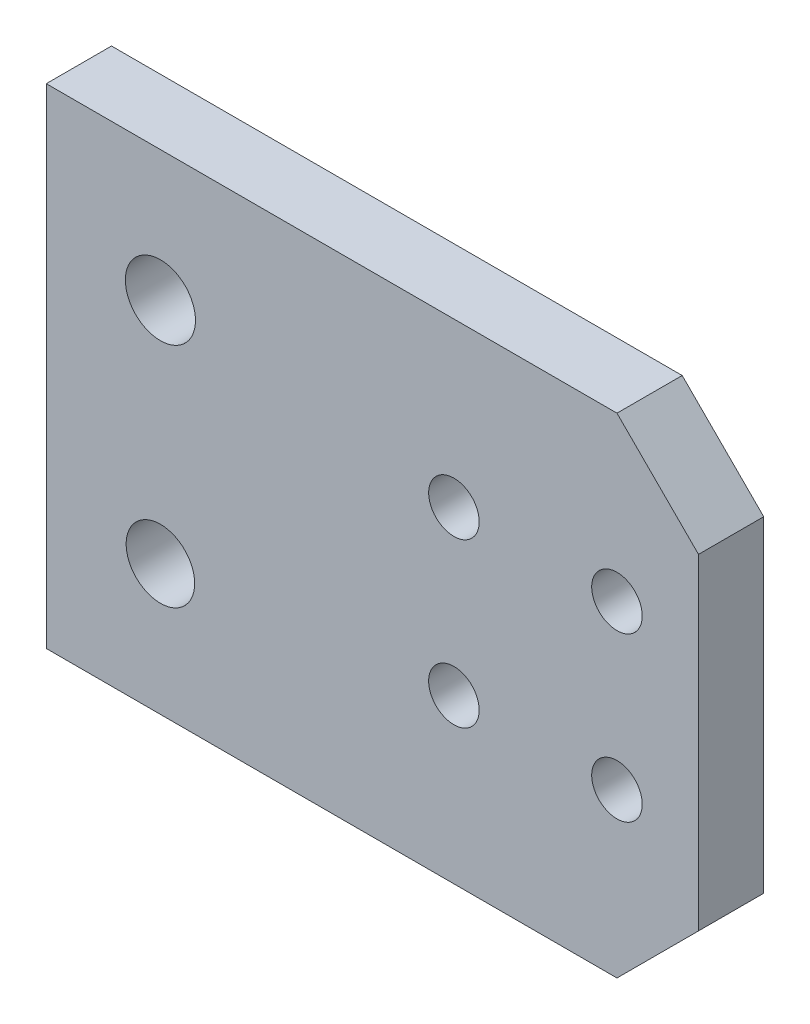
SolidWorks part; units mm, degrees
material "Thornel Mat VMA"
ref_plane "前视基准面" through (0, 0, 0) normal (0, 0, 1) x (1, 0, 0)
ref_plane "上视基准面" through (0, 0, 0) normal (0, 1, 0) x (1, 0, 0)
ref_plane "右视基准面" through (0, 0, 0) normal (1, 0, 0) x (0, 0, -1)
other "Configuration Table"
sketch "草图1" plane through (0, 0, 0) normal (0, 0, 1) x (1, 0, 0)
  line L0 (0, 15) -> (40, 15) construction
  line L1 (0, 0) -> (40, 0)
  line L2 (0, 0) -> (0, 30)
  line L3 (0, 30) -> (40, 30)
  line L4 (40, 0) -> (40, 30)
  circle A0 centre (7, 22) radius 2.15
  circle A1 centre (7, 8) radius 2.1
  circle A2 centre (35, 20) radius 1.55
  circle A3 centre (25, 20) radius 1.55
  circle A4 centre (25, 10) radius 1.55
  circle A5 centre (35, 10) radius 1.55
  point P9 (0, 15)
  dimension "D5" = 4.3
  dimension "D6" = 4.2
  dimension "D9" = 3.1
  dimension "D1" = 30
  dimension "D2" = 40
  dimension "D3" = 7
  dimension "D4" = 7
  dimension "D7" = 7
  dimension "D8" = 7
  dimension "D10" = 5
  dimension "D11" = 5
  dimension "D12" = 2
  dimension "D13" = 2
extrude "凸台-拉伸1" add sketch "草图1" along normal blind 4
chamfer "倒角1" distance 5 angle 45 2 edges at (40, 0, 2) (40, 30, 2)
